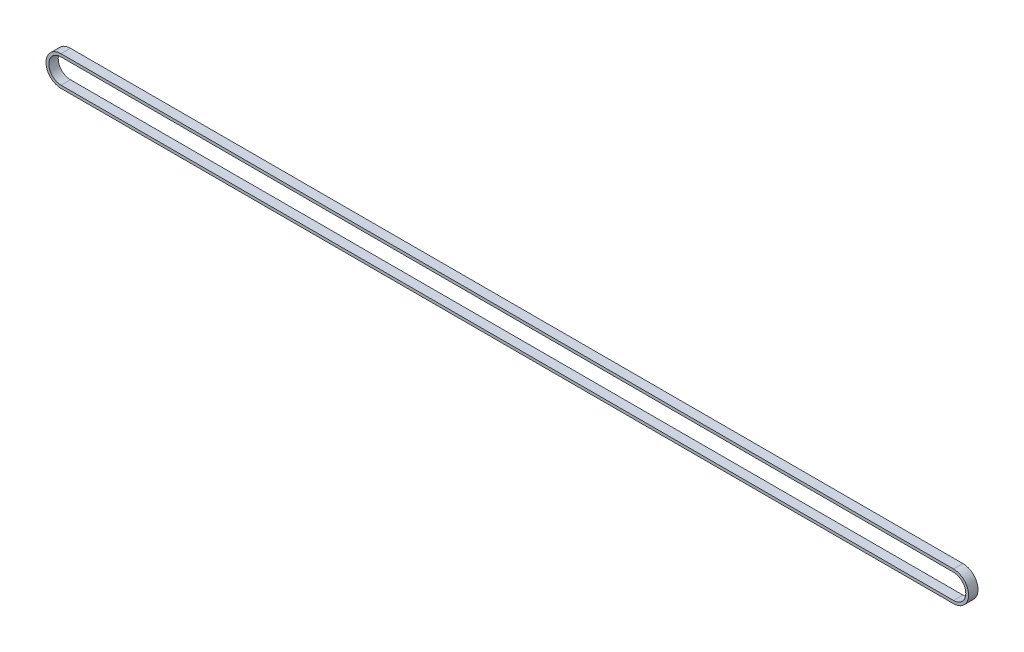
SolidWorks part; units mm, degrees
ref_plane "Front Plane" through (0, 0, 0) normal (0, 0, 1) x (1, 0, 0)
ref_plane "Top Plane" through (0, 0, 0) normal (0, 1, 0) x (1, 0, 0)
ref_plane "Right Plane" through (0, 0, 0) normal (1, 0, 0) x (0, 0, -1)
sketch "Sketch1" plane through (0, 0, 0) normal (0, 0, 1) x (1, 0, 0)
  line L0 (0, 0) -> (474.5, 0) construction
  line L1 (0, 6.5) -> (474.5, 6.5)
  line L2 (0, -6.5) -> (474.5, -6.5)
  line L3 (0, 8) -> (474.5, 8)
  line L4 (0, -8) -> (474.5, -8)
  arc A0 (0, 6.5) -> (0, -6.5) centre (0, 0) ccw
  arc A1 (474.5, -6.5) -> (474.5, 6.5) centre (474.5, 0) ccw
  arc A2 (474.5, -8) -> (474.5, 8) centre (474.5, 0) ccw
  arc A3 (0, 8) -> (0, -8) centre (0, 0) ccw
  point P3 (237.25, 0)
  dimension "D1" = 13
  dimension "D2" = 474.5
  dimension "D3" = 1.5
extrude "Boss-Extrude1" add sketch "Sketch1" along normal blind 5
